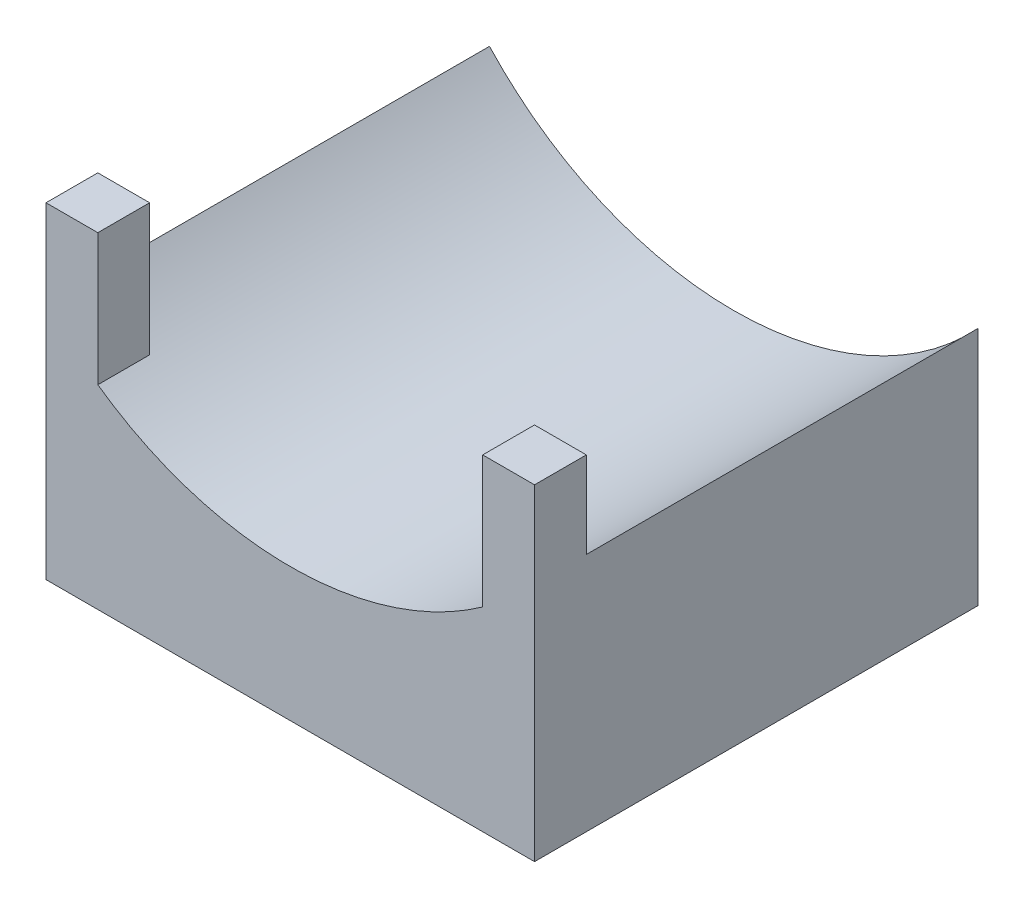
SolidWorks part; units mm, degrees
ref_plane "Front Plane" through (0, 0, 0) normal (0, 0, 1) x (1, 0, 0)
ref_plane "Top Plane" through (0, 0, 0) normal (0, 1, 0) x (1, 0, 0)
ref_plane "Right Plane" through (0, 0, 0) normal (1, 0, 0) x (0, 0, -1)
sketch "Sketch2" plane through (0, 0, 0) normal (0, 0, 1) x (1, 0, 0)
  line L1 (-7.4837, -6.9307) -> (-7.4837, -14.2875)
  line L2 (-7.4837, -14.2875) -> (7.4837, -14.2875)
  line L3 (7.4837, -14.2875) -> (7.4837, -6.9307)
  line L4 (-7.4837, -6.9307) -> (-7.4837, -14.2875)
  line L5 (7.4837, -6.9307) -> (7.4837, -14.2875)
  arc A0 (-7.4837, -6.9307) -> (7.4837, -6.9307) centre (0, 0) ccw
  arc A1 (-7.4837, -6.9307) -> (7.4837, -6.9307) centre (0, 0) ccw
  point P8 (0, -10.2)
  point P9 (0, -14.2875)
  dimension "D1" = 20.4
  dimension "D2" = 14.9674
  dimension "D3" = 4.0875
  dimension "D4" = 7.3568
extrude "Boss-Extrude1" add sketch "Sketch2" along normal blind 12 contours A0 L1 L2 L3
sketch "Sketch3" plane through (0, 0, 12) normal (0, 0, 1) x (1, 0, 0)
  line L1 (-7.4837, -14.2875) -> (-5.8962, -14.2875)
  line L2 (-7.4837, -14.2875) -> (-7.4837, -4.2875)
  line L3 (-7.4837, -4.2875) -> (-5.8962, -4.2875)
  line L4 (-5.8962, -14.2875) -> (-5.8962, -4.2875)
  line L5 (7.4837, -14.2875) -> (5.8962, -14.2875)
  line L6 (7.4837, -14.2875) -> (7.4837, -4.2875)
  line L7 (7.4837, -4.2875) -> (5.8962, -4.2875)
  line L8 (5.8962, -14.2875) -> (5.8962, -4.2875)
  dimension "D1" = 10
  dimension "D2" = 1.5875
  dimension "D3" = 1.5875
  dimension "D4" = 10
extrude "Boss-Extrude2" add sketch "Sketch3" along normal blind 1.5875
sketch "Sketch4" plane through (0, 0, 12) normal (0, 0, 1) x (1, 0, 0)
  line L0 (-5.8962, -8.3231) -> (-5.8962, -14.2875)
  line L1 (-5.8962, -14.2875) -> (5.8962, -14.2875)
  line L2 (5.8962, -14.2875) -> (5.8962, -8.3231)
  arc A0 (-5.8962, -8.3231) -> (5.8962, -8.3231) centre (0, 0) ccw
extrude "Boss-Extrude3" add sketch "Sketch4" along normal blind 1.5875
